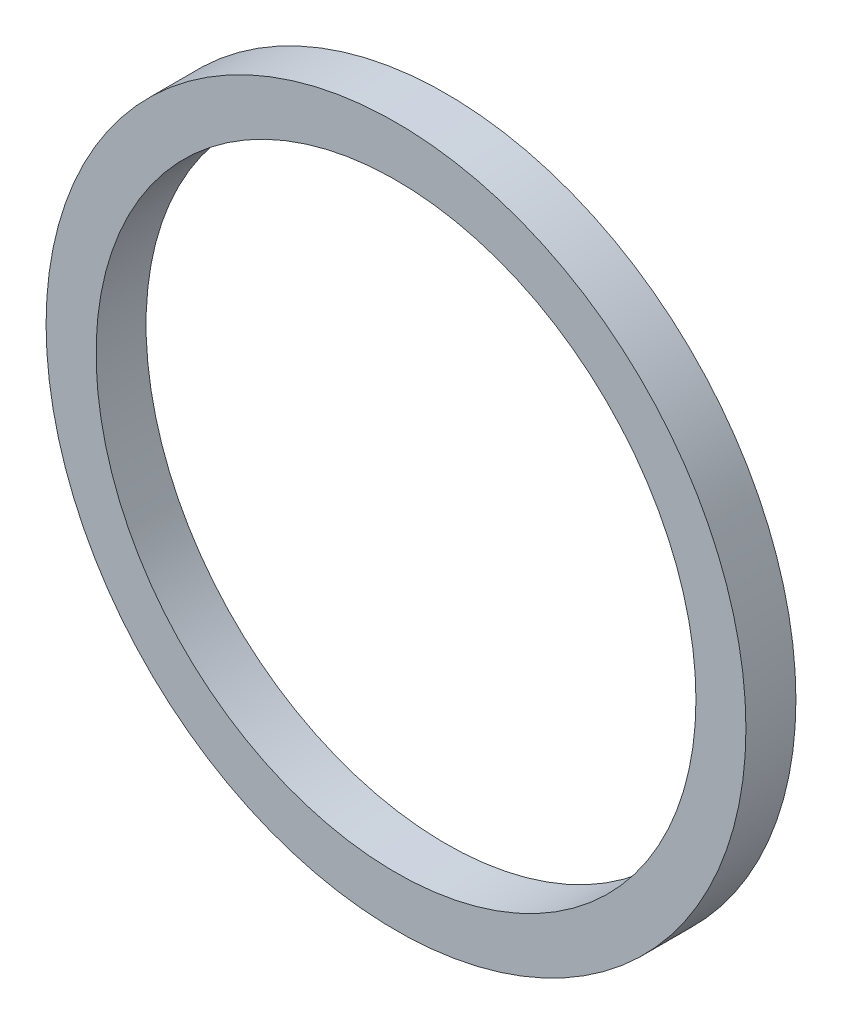
SolidWorks part; units mm, degrees
ref_plane "Front Plane" through (0, 0, 0) normal (0, 0, 1) x (1, 0, 0)
ref_plane "Top Plane" through (0, 0, 0) normal (0, 1, 0) x (1, 0, 0)
ref_plane "Right Plane" through (0, 0, 0) normal (1, 0, 0) x (0, 0, -1)
sketch "Sketch1" plane through (0, 0, 0) normal (0, 0, 1) x (1, 0, 0)
  circle A0 centre (0, 0) radius 35
  circle A1 centre (0, 0) radius 30
  dimension "D1" = 60
  dimension "D2" = 70
extrude "Boss-Extrude1" add sketch "Sketch1" along normal blind 5
